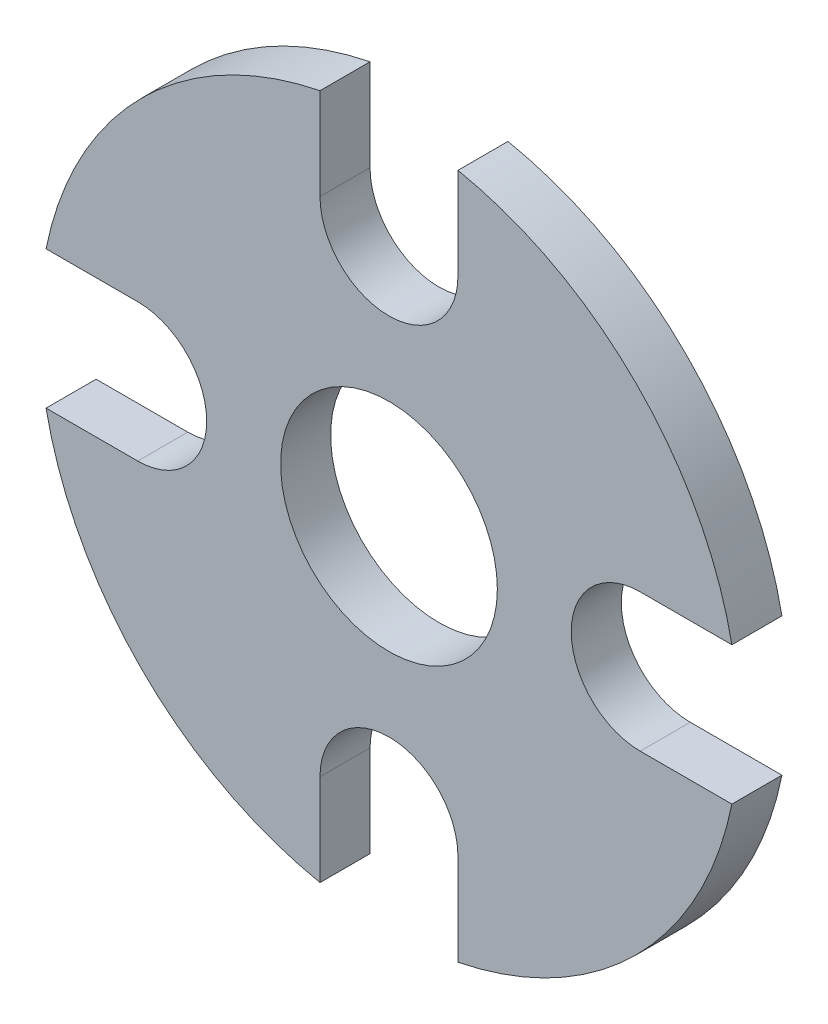
SolidWorks part; units mm, degrees
ref_plane "Front Plane" through (0, 0, 0) normal (0, 0, 1) x (1, 0, 0)
ref_plane "Top Plane" through (0, 0, 0) normal (0, 1, 0) x (1, 0, 0)
ref_plane "Right Plane" through (0, 0, 0) normal (1, 0, 0) x (0, 0, -1)
sketch "Sketch1" plane through (0, 0, 0) normal (0, 0, 1) x (1, 0, 0)
  line L0 (0, 455) -> (0, 255) construction
  line L1 (70, 455) -> (70, 255)
  line L2 (-70, 455) -> (-70, 255)
  line L3 (455, 0) -> (255, 0) construction
  line L4 (455, -70) -> (255, -70)
  line L5 (455, 70) -> (255, 70)
  line L6 (0, -455) -> (0, -255) construction
  line L7 (-70, -455) -> (-70, -255)
  line L8 (70, -455) -> (70, -255)
  line L9 (-455, 0) -> (-255, 0) construction
  line L10 (-455, 70) -> (-255, 70)
  line L11 (-455, -70) -> (-255, -70)
  circle A0 centre (0, 0) radius 355
  arc A1 (70, 455) -> (-70, 455) centre (0, 455) ccw
  arc A2 (-70, 255) -> (70, 255) centre (0, 255) ccw
  arc A3 (455, -70) -> (455, 70) centre (455, 0) ccw
  arc A4 (255, 70) -> (255, -70) centre (255, 0) ccw
  arc A5 (-70, -455) -> (70, -455) centre (0, -455) ccw
  arc A6 (70, -255) -> (-70, -255) centre (0, -255) ccw
  arc A7 (-455, 70) -> (-455, -70) centre (-455, 0) ccw
  arc A8 (-255, -70) -> (-255, 70) centre (-255, 0) ccw
  point P5 (0, 355)
  point P10 (0, 185)
  point P16 (355, 0)
  point P23 (0, -355)
  point P30 (-355, 0)
  point P35 (0, 0)
  dimension "D1" = 710
  dimension "D3" = 70
  dimension "D2" = 170
  dimension "D4" = 4
extrude "Boss-Extrude1" add sketch "Sketch1" along normal blind 50.8 contours A8 L11 A0 L7 A6 L8 L4 A4 L5 L1 A2 L2 L10
sketch "Sketch2" plane through (0, 0, 50.8) normal (0, 0, 1) x (1, 0, 0)
  circle A0 centre (0, 0) radius 110
  dimension "D1" = 220
extrude "Cut-Extrude1" cut sketch "Sketch2" against normal through all
